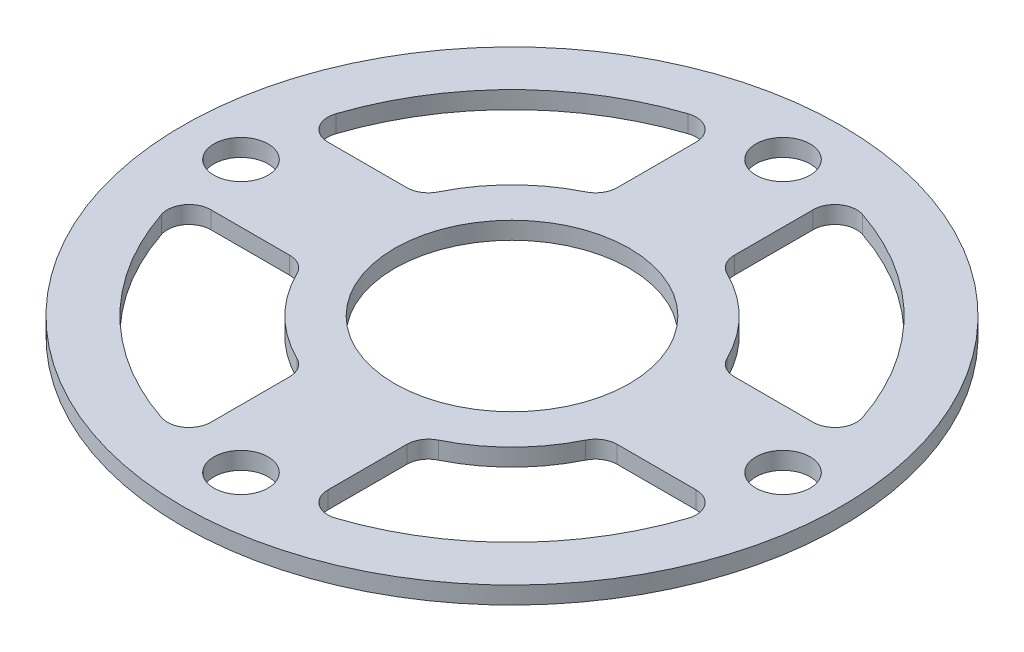
SolidWorks part; units mm, degrees
material "Custom Plastic"
ref_plane "Front Plane" through (0, 0, 0) normal (0, 0, 1) x (1, 0, 0)
ref_plane "Top Plane" through (0, 0, 0) normal (0, 1, 0) x (1, 0, 0)
ref_plane "Right Plane" through (0, 0, 0) normal (1, 0, 0) x (0, 0, -1)
sketch "Sketch1" plane through (0, 0, 0) normal (0, 1, 0) x (1, 0, 0)
  circle A0 centre (0, 0) radius 76
  circle A1 centre (0, 0) radius 27.051
  circle A2 centre (0, 0) radius 62.5 construction
  circle A3 centre (0, 62.5) radius 6.25
  circle A4 centre (62.5, 0) radius 6.25
  circle A5 centre (0, -62.5) radius 6.25
  circle A6 centre (-62.5, 0) radius 6.25
  dimension "D1" = 152
  dimension "D2" = 54.102
  dimension "D3" = 125
  dimension "D4" = 12.5
extrude "Boss-Extrude1" add sketch "Sketch1" along normal blind 4
sketch "Sketch3" plane through (0, 0, 0) normal (0, -1, 0) x (1, 0, 0)
  circle A0 centre (0, 0) radius 27.051
sketch "Sketch4" plane through (0, 4, 0) normal (0, 1, 0) x (1, 0, 0)
  line L0 (134.0846, 0) -> (0, 0) construction
  line L1 (0, 0) -> (0, 97.8812) construction
  line L2 (13.5, 62.5) -> (13.5, 34.504)
  line L3 (34.504, 13.5) -> (62.5, 13.5)
  line L4 (-34.504, 13.5) -> (-62.5, 13.5)
  line L5 (-13.5, 62.5) -> (-13.5, 34.504)
  line L6 (34.504, -13.5) -> (62.5, -13.5)
  line L7 (13.5, -62.5) -> (13.5, -34.504)
  line L8 (-13.5, -62.5) -> (-13.5, -34.504)
  line L9 (-34.504, -13.5) -> (-62.5, -13.5)
  arc A0 (13.5, 62.5) -> (62.5, 13.5) centre (0, 0) cw
  arc A7 (-13.5, 62.5) -> (-62.5, 13.5) centre (0, 0) ccw
  arc A8 (13.5, -62.5) -> (62.5, -13.5) centre (0, 0) ccw
  arc A10 (-13.5, -62.5) -> (-62.5, -13.5) centre (0, 0) cw
  circle A11 centre (0, 0) radius 37.051
  circle A12 centre (0, 0) radius 27.051 construction
  dimension "D1" = 10
  dimension "D4" = 63.9414
  dimension "D2" = 27
  dimension "D3" = 27
extrude "Cut-Extrude2" cut sketch "Sketch4" against normal through all contours A11 L5 A7 L4 | A11 L3 A0 L2 | A11 L7 A8 L6 | A11 L9 A10 L8
fillet "Fillet1" radius 5 16 edges at (-13.5, 2, 34.504) (-13.5, 2, 62.5) (-34.504, 2, 13.5) (-62.5, 2, 13.5) (13.5, 2, 62.5) (13.5, 2, 34.504) (34.504, 2, 13.5) (62.5, 2, 13.5) (34.504, 2, -13.5) (13.5, 2, -34.504) (62.5, 2, -13.5) (13.5, 2, -62.5) (-62.5, 2, -13.5) (-34.504, 2, -13.5) (-13.5, 2, -34.504) (-13.5, 2, -62.5)
